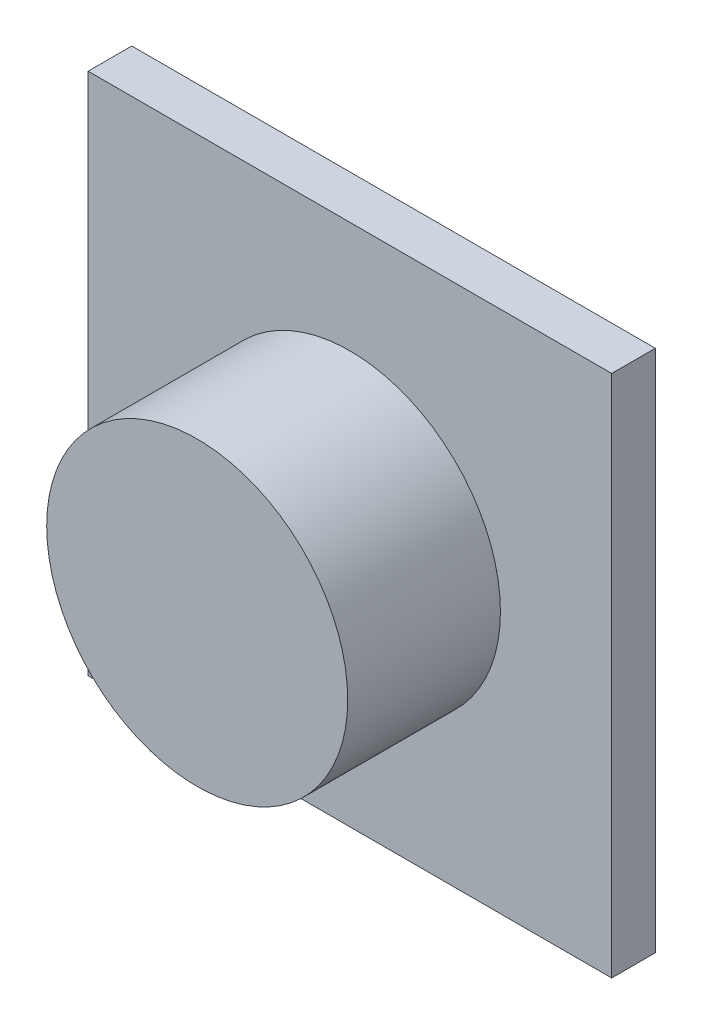
SolidWorks part; units mm, degrees
ref_plane "Front Plane" through (0, 0, 0) normal (0, 0, 1) x (1, 0, 0)
ref_plane "Top Plane" through (0, 0, 0) normal (0, 1, 0) x (1, 0, 0)
ref_plane "Right Plane" through (0, 0, 0) normal (1, 0, 0) x (0, 0, -1)
sketch "Sketch1" plane through (0, 0, 0) normal (0, 0, 1) x (1, 0, 0)
  line L1 (-10.3426, 6.1633) -> (1.6574, 6.1633)
  line L2 (-10.3426, 6.1633) -> (-10.3426, -5.8367)
  line L3 (-10.3426, -5.8367) -> (1.6574, -5.8367)
  line L4 (1.6574, 6.1633) -> (1.6574, -5.8367)
  dimension "D1" = 12
  dimension "D2" = 12
extrude "Boss-Extrude1" add sketch "Sketch1" along normal blind 1 contours L2 L1 L4 L3
sketch "Sketch2" plane through (0, 0, 1) normal (0, 0, 1) x (1, 0, 0)
  line L0 (-4.3426, 0.1633) -> (-4.3426, 6.1633) construction
  line L1 (-10.3426, 6.1633) -> (1.6574, 6.1633) construction
  line L2 (-4.3426, 0.1633) -> (-10.3426, 0.1633) construction
  line L3 (-10.3426, 6.1633) -> (-10.3426, -5.8367) construction
  circle A0 centre (-4.3426, 0.1633) radius 3.45
  dimension "D1" = 6.9
extrude "Boss-Extrude2" add sketch "Sketch2" along normal blind 3.5
